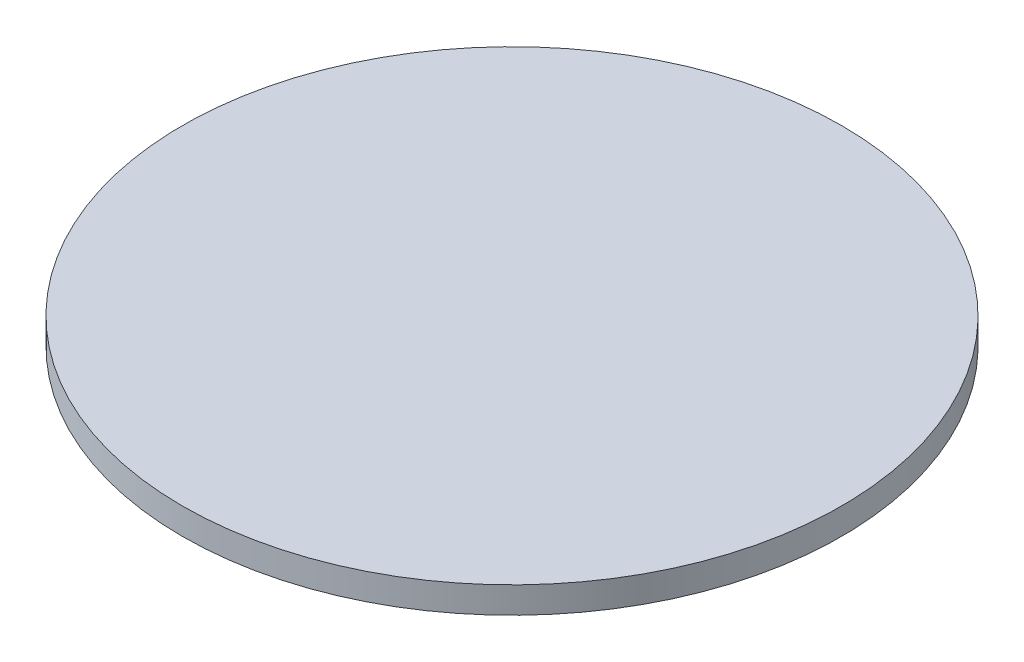
SolidWorks part; units mm, degrees
ref_plane "Front Plane" through (0, 0, 0) normal (0, 0, 1) x (1, 0, 0)
ref_plane "Top Plane" through (0, 0, 0) normal (0, 1, 0) x (1, 0, 0)
ref_plane "Right Plane" through (0, 0, 0) normal (1, 0, 0) x (0, 0, -1)
sketch "Sketch1" plane through (0, 0, 0) normal (0, 1, 0) x (1, 0, 0)
  circle A0 centre (0, 0) radius 125
  dimension "D1" = 250
extrude "Boss-Extrude1" add sketch "Sketch1" along normal blind 10
